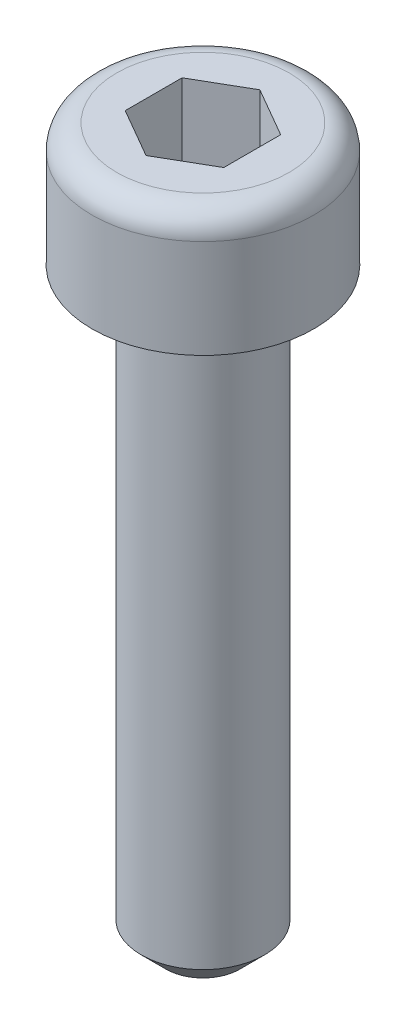
SolidWorks part; units mm, degrees
material "acero"
ref_plane "Alzado" through (0, 0, 0) normal (0, 0, 1) x (1, 0, 0)
ref_plane "Planta" through (0, 0, 0) normal (0, 1, 0) x (1, 0, 0)
ref_plane "Vista lateral" through (0, 0, 0) normal (1, 0, 0) x (0, 0, -1)
sketch "Croquis1" plane through (0, 0, 0) normal (0, 0, 1) x (1, 0, 0)
  line L0 (0, 0) -> (0, -60.9498) construction
  line L1 (0, 0) -> (2.25, 0)
  line L2 (2.25, 0) -> (2.25, -2.5)
  line L3 (2.25, -2.5) -> (1.25, -2.5)
  line L4 (1.25, -2.5) -> (1.25, -14.5)
  line L5 (1.25, -14.5) -> (0, -14.5)
  line L6 (0, -14.5) -> (0, 0)
  dimension "D1" = 12
  dimension "D2" = 2.5
  dimension "D3" = 4.5
  dimension "D4" = 2.5
revolve "Revolución1" add sketch "Croquis1" angle 360 about L0
sketch "Croquis2" plane through (0, 0, 0) normal (0, 1, 0) x (1, 0, 0)
  line L1 (1, 0.5774) -> (0, 1.1547)
  line L2 (0, 1.1547) -> (-1, 0.5774)
  line L3 (-1, 0.5774) -> (-1, -0.5774)
  line L4 (-1, -0.5774) -> (0, -1.1547)
  line L5 (0, -1.1547) -> (1, -0.5774)
  line L6 (1, -0.5774) -> (1, 0.5774)
  circle A0 centre (0, 0) radius 1 construction
  dimension "D1" = 2
extrude "Cortar-Extruir1" cut sketch "Croquis2" against normal blind 2
chamfer "Chaflán1" distance 0.5 angle 45 1 edges at (0, -14.5, 1.25)
fillet "Redondeo1" radius 0.5 1 edges at (0, 0, 2.25)
